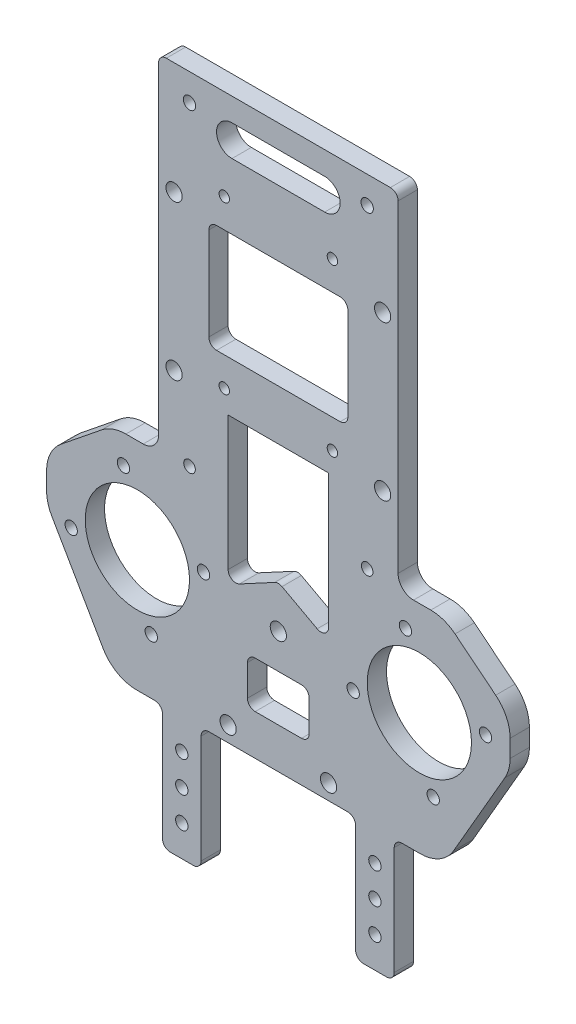
SolidWorks part; units mm, degrees
material "Thornel Mat VMA"
ref_plane "前视基准面" through (0, 0, 0) normal (0, 0, 1) x (1, 0, 0)
ref_plane "上视基准面" through (0, 0, 0) normal (0, 1, 0) x (1, 0, 0)
ref_plane "右视基准面" through (0, 0, 0) normal (1, 0, 0) x (0, 0, -1)
sketch "草图1" plane through (0, 0, 0) normal (0, 0, 1) x (1, 0, 0)
  line L0 (0, 0) -> (0, 157.5301) construction
  line L1 (-42.5, -55.5) -> (-30, -55.5)
  line L2 (43, 0.5) -> (60, -13.1891)
  line L3 (-10.5, -55.5) -> (10.5, -55.5) construction
  line L4 (42.5, -55.5) -> (60, -25.1891)
  line L5 (60, -25.1891) -> (60, -13.1891)
  line L6 (43, 0.5) -> (31, 0.5)
  line L7 (31, 0.5) -> (31, 88)
  line L8 (29, 90) -> (-29, 90)
  line L9 (-31, 0.5) -> (-31, 88)
  line L10 (-43, 0.5) -> (-31, 0.5)
  line L11 (-60, -25.1891) -> (-60, -13.1891)
  line L12 (-42.5, -55.5) -> (-60, -25.1891)
  line L13 (-43, 0.5) -> (-60, -13.1891)
  line L14 (-30, -55.5) -> (-30, -87.5)
  line L15 (-30, -87.5) -> (-20, -87.5)
  line L16 (-20, -87.5) -> (-20, -55.5)
  line L17 (-20, -55.5) -> (20, -55.5)
  line L18 (30, -87.5) -> (20, -87.5)
  line L19 (20, -87.5) -> (20, -55.5)
  line L20 (30, -55.5) -> (30, -87.5)
  line L21 (30, -55.5) -> (42.5, -55.5)
  line L22 (-25, -87.5) -> (-25, -52.5) construction
  circle A0 centre (36.5, -24) radius 13.5
  circle A1 centre (32.9025, -6.8738) radius 1.6
  circle A2 centre (53.6262, -20.4025) radius 1.6
  circle A3 centre (19.3738, -27.5975) radius 1.6
  circle A4 centre (40.0975, -41.1262) radius 1.6
  circle A5 centre (-36.5, -24) radius 13.5
  circle A6 centre (-40.0975, -6.8738) radius 1.6
  circle A7 centre (-19.3738, -20.4025) radius 1.6
  circle A8 centre (-32.9025, -41.1262) radius 1.6
  circle A9 centre (-53.6262, -27.5975) radius 1.6
  circle A10 centre (-13, -51.5) radius 2.1
  circle A11 centre (13, -51.5) radius 2.1
  circle A12 centre (0, -24) radius 2.1
  circle A13 centre (27, 21) radius 2.1
  circle A14 centre (27, 61) radius 2.1
  circle A15 centre (-27, 21) radius 2.1
  circle A16 centre (-27, 61) radius 2.1
  circle A17 centre (-25, -79.5) radius 1.6
  circle A18 centre (-25, -63.5) radius 1.6
  circle A19 centre (-25, -71.5) radius 1.6
  circle A20 centre (25, -79.5) radius 1.6
  circle A21 centre (25, -71.5) radius 1.6
  circle A22 centre (25, -63.5) radius 1.6
  circle A23 centre (14, 23.5) radius 1.35
  circle A24 centre (-14, 23.5) radius 1.35
  circle A25 centre (14, 66.5) radius 1.35
  circle A26 centre (-14, 66.5) radius 1.35
  circle A27 centre (-23, 83) radius 1.6
  circle A28 centre (23, 83) radius 1.6
  arc A29 (31, 88) -> (29, 90) centre (29, 88) ccw
  arc A30 (-31, 88) -> (-29, 90) centre (-29, 88) cw
  circle A31 centre (23, 1.5) radius 1.5 construction
  circle A32 centre (-23, 1.5) radius 1.5 construction
  circle A33 centre (23, 1.5) radius 1.5
  circle A34 centre (-23, 1.5) radius 1.5
  point P13 (0, 90)
  point P17 (0, -55.5)
  point P110 (31, 90)
  point P113 (-31, 90)
  dimension "D1" = 27
  dimension "D2" = 3.2
  dimension "D3" = 3.2
  dimension "D4" = 3.2
  dimension "D5" = 3.2
  dimension "D6" = 3.2
  dimension "D7" = 3.2
  dimension "D8" = 3.2
  dimension "D9" = 27
  dimension "D10" = 3.2
  dimension "D11" = 4.2
  dimension "D12" = 4.2
  dimension "D13" = 4.2
  dimension "D21" = 4.2
  dimension "D22" = 4.2
  dimension "D28" = 8
  dimension "D31" = 3.2
  dimension "D32" = 3.2
  dimension "D33" = 3.2
  dimension "D34" = 2.7
  dimension "D35" = 2.7
  dimension "D36" = 2.7
  dimension "D37" = 2.7
  dimension "D38" = 3.2
  dimension "D39" = 3.2
  dimension "D40" = 2
  dimension "D14" = 31
  dimension "D15" = 85
  dimension "D16" = 120
  dimension "D17" = 60
  dimension "D18" = 56
  dimension "D19" = 12
  dimension "D20" = 12
  dimension "D23" = 90
  dimension "D24" = 20
  dimension "D25" = 10
  dimension "D26" = 32
  dimension "D27" = 55.5
  dimension "D29" = 8
  dimension "D30" = 8
extrude "凸台-拉伸1" add sketch "草图1" along normal blind 5
fillet "圆角1" radius 10 8 edges at (43, 0.5, 2.5) (60, -13.1891, 2.5) (60, -25.1891, 2.5) (-43, 0.5, 2.5) (-60, -13.1891, 2.5) (-60, -25.1891, 2.5) (-42.5, -55.5, 2.5) (42.5, -55.5, 2.5)
fillet "圆角2" radius 4 2 edges at (31, 0.5, 2.5) (-31, 0.5, 2.5)
fillet "圆角3" radius 2 8 edges at (-30, -55.5, 2.5) (-30, -87.5, 2.5) (-20, -87.5, 2.5) (-20, -55.5, 2.5) (20, -55.5, 2.5) (20, -87.5, 2.5) (30, -87.5, 2.5) (30, -55.5, 2.5)
sketch "草图2" plane through (0, 0, 5) normal (0, 0, 1) x (1, 0, 0)
  line L0 (0, 0) -> (0, 96.9872) construction
  line L1 (10.0518, -18.4125) -> (0.9482, -13.5106)
  line L2 (13, -16.6516) -> (13, -2)
  line L3 (11, 0) -> (-11, 0)
  line L4 (-13, -16.6516) -> (-13, -2)
  line L5 (-10.0518, -18.4125) -> (-0.9482, -13.5106)
  line L6 (-8, -35) -> (-8, -43)
  line L7 (-6, -45) -> (6, -45)
  line L8 (8, -43) -> (8, -35)
  line L9 (6, -33) -> (-6, -33)
  line L10 (-16, 59) -> (16, 59)
  line L11 (18, 57) -> (18, 33)
  line L12 (16, 31) -> (-16, 31)
  line L13 (-18, 33) -> (-18, 57)
  line L14 (-12, 80) -> (12, 80) construction
  line L15 (-12, 84) -> (12, 84)
  line L16 (-12, 76) -> (12, 76)
  arc A0 (13, -2) -> (11, 0) centre (11, -2) ccw
  arc A1 (-13, -2) -> (-11, 0) centre (-11, -2) cw
  arc A2 (-13, -16.6516) -> (-10.0518, -18.4125) centre (-11, -16.6516) ccw
  arc A3 (0.9482, -13.5106) -> (-0.9482, -13.5106) centre (0, -15.2715) ccw
  arc A4 (10.0518, -18.4125) -> (13, -16.6516) centre (11, -16.6516) ccw
  arc A5 (-8, -43) -> (-6, -45) centre (-6, -43) ccw
  arc A6 (6, -45) -> (8, -43) centre (6, -43) ccw
  arc A7 (8, -35) -> (6, -33) centre (6, -35) ccw
  arc A8 (-8, -35) -> (-6, -33) centre (-6, -35) cw
  arc A9 (-16, 31) -> (-18, 33) centre (-16, 33) cw
  arc A10 (18, 33) -> (16, 31) centre (16, 33) cw
  arc A11 (16, 59) -> (18, 57) centre (16, 57) cw
  arc A12 (-16, 59) -> (-18, 57) centre (-16, 57) ccw
  arc A13 (-12, 84) -> (-12, 76) centre (-12, 80) ccw
  arc A14 (12, 76) -> (12, 84) centre (12, 80) ccw
  point P11 (13, 0)
  point P14 (-13, 0)
  point P17 (-13, -20)
  point P20 (0, -13)
  point P23 (13, -20)
  point P29 (-8, -45)
  point P36 (-8, -33)
  point P43 (-18, 31)
  point P50 (-18, 59)
  point P53 (0, 80)
  dimension "D4" = 2
  dimension "D9" = 2
  dimension "D14" = 2
  dimension "D1" = 13
  dimension "D2" = 20
  dimension "D3" = 13
  dimension "D5" = 8
  dimension "D6" = 8
  dimension "D7" = 33
  dimension "D8" = 12
  dimension "D10" = 31
  dimension "D11" = 18
  dimension "D12" = 18
  dimension "D13" = 28
  dimension "D15" = 21
  dimension "D16" = 8
  dimension "D17" = 24
extrude "切除-拉伸1" cut sketch "草图2" against normal through all
sketch "草图3" plane through (0, 0, 5) normal (0, 0, 1) x (1, 0, 0)
  line L0 (-13, -2) -> (-13, 18)
  line L1 (13, -2) -> (13, 18)
  line L2 (13, 18) -> (-13, 18)
  line L3 (-13, -2) -> (13, -2)
  dimension "D1" = 20
extrude "切除-拉伸2" cut sketch "草图3" against normal through all
